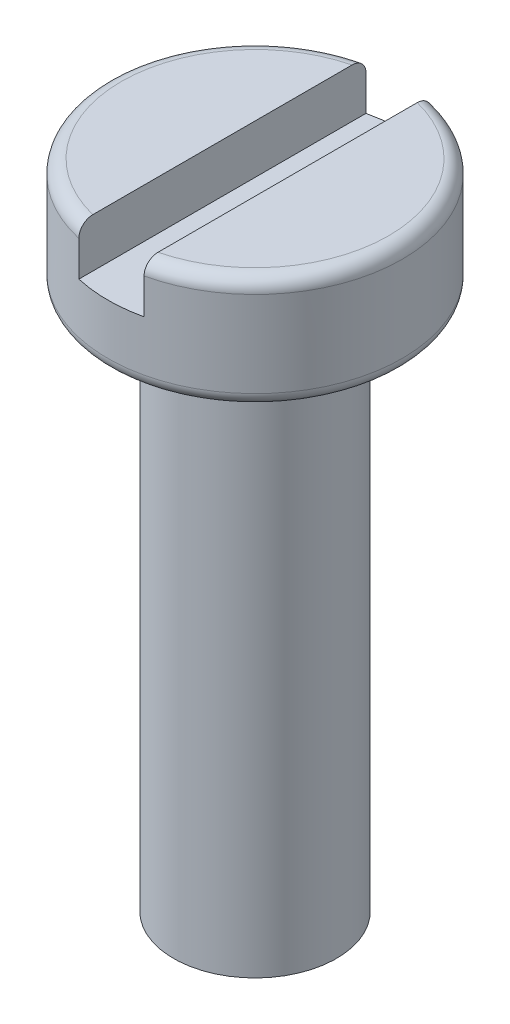
SolidWorks part; units mm, degrees
material "Plain Carbon Steel"
ref_plane "Front Plane" through (0, 0, 0) normal (0, 0, 1) x (1, 0, 0)
ref_plane "Top Plane" through (0, 0, 0) normal (0, 1, 0) x (1, 0, 0)
ref_plane "Right Plane" through (0, 0, 0) normal (1, 0, 0) x (0, 0, -1)
sketch "Sketch1" plane through (0, 0, 0) normal (0, 1, 0) x (1, 0, 0)
  circle A0 centre (0, 0) radius 2.71
  dimension "D1" = 5.42
extrude "Boss-Extrude1" add sketch "Sketch1" along normal blind 12
sketch "Sketch2" plane through (0, 12, 0) normal (0, 1, 0) x (1, 0, 0)
  circle A0 centre (0, 0) radius 1.5
  dimension "D1" = 3
extrude "Cut-Extrude1" cut sketch "Sketch2" against normal blind 9.92 flip side to cut
cosmetic thread "Cosmetic Thread1" parameters "D2"=2.439
fillet "Fillet1" radius 0.25 2 edges at (0, 0, 2.71) (0, 2.08, 2.71)
fillet "Fillet2" radius 0.15 1 edges at (0, 2.08, 1.5)
sketch "Sketch3" plane through (0, 0, 0) normal (0, -1, 0) x (1, 0, 0)
  line L0 (0, 2.71) -> (0, -2.71) construction
  line L1 (-0.6, -2.711) -> (-0.6, 2.711)
  line L2 (-0.6, -2.711) -> (0.6, -2.711)
  line L3 (-0.6, 2.711) -> (0.6, 2.711)
  line L4 (0.6, -2.711) -> (0.6, 2.711)
  line L5 (-0.6, -2.711) -> (0.6, 2.711) construction
  line L6 (-0.6, 2.711) -> (0.6, -2.711) construction
  circle A0 centre (0, 0) radius 2.71 construction
  point P6 (0, 0)
  dimension "D1" = 0.6
extrude "Cut-Extrude2" cut sketch "Sketch3" against normal blind 0.9
move or copy body "Body-Move/Copy1" bodies to move or copy 103 copy no rotation origin (0, 10, 0) rotation axis (1, 0, 0) rotation angle 180
